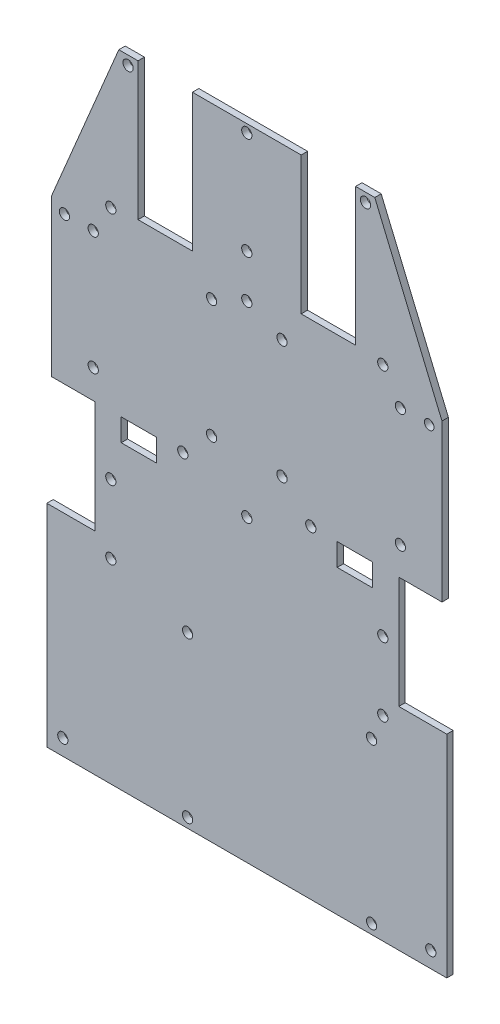
SolidWorks part; units mm, degrees
ref_plane "前基準面" through (0, 0, 0) normal (0, 0, 1) x (1, 0, 0)
ref_plane "上基準面" through (0, 0, 0) normal (0, 1, 0) x (1, 0, 0)
ref_plane "右基準面" through (0, 0, 0) normal (1, 0, 0) x (0, 0, -1)
sketch "草圖1" plane through (0, 0, 0) normal (0, 0, 1) x (1, 0, 0)
  line L0 (-42.5, 0) -> (42.5, 0)
  line L1 (-42.5, 0) -> (-42.5, 56)
  line L2 (-42.5, 56) -> (42.5, 56)
  line L3 (42.5, 56) -> (42.5, 0)
  line L4 (42.5, 0) -> (62.5, 0)
  line L5 (-42.5, 0) -> (-62.5, 0)
  line L6 (-62.5, 0) -> (-62.5, 66)
  line L7 (62.5, 0) -> (62.5, 66)
  line L8 (-62.5, 66) -> (-47.5, 66)
  line L9 (62.5, 66) -> (47.5, 66)
  line L10 (-47.5, 66) -> (-47.5, 101)
  line L12 (47.5, 101) -> (47.5, 66)
  line L16 (-62.5, 0) -> (-90.3643, 0)
  line L17 (-90.3643, 0) -> (-90.3643, 200)
  line L18 (-47.5, 101) -> (-61, 101)
  line L19 (47.5, 101) -> (61, 101)
  line L28 (-61, 101) -> (-61, 150)
  line L29 (-39.25, 101) -> (-28.25, 101)
  line L30 (39.25, 94) -> (28.25, 94)
  line L31 (-39.25, 101) -> (-39.25, 94)
  line L32 (-39.25, 94) -> (-28.25, 94)
  line L33 (-28.25, 101) -> (-28.25, 94)
  line L34 (28.25, 101) -> (28.25, 94)
  line L35 (39.25, 101) -> (28.25, 101)
  line L36 (39.25, 101) -> (39.25, 94)
  line L37 (61, 101) -> (61, 150)
  line L38 (62.5, 0) -> (90.3643, 0)
  line L39 (90.3643, 0) -> (90.3643, 200)
  line L40 (51, 107) -> (8, 107)
  line L41 (-51, 150) -> (-8, 150)
  line L42 (34, 200) -> (40, 200)
  line L43 (-51, 150) -> (-51, 107)
  line L44 (-51, 107) -> (-8, 107)
  line L45 (-8, 150) -> (-8, 107)
  line L46 (8, 150) -> (8, 107)
  line L47 (51, 150) -> (8, 150)
  line L48 (51, 150) -> (51, 107)
  line L49 (-17, 157) -> (-17, 200)
  line L50 (17, 157) -> (17, 200)
  line L52 (17, 157) -> (34, 157)
  line L53 (34, 157) -> (34, 200)
  line L54 (40, 200) -> (61, 150)
  line L55 (-90.3643, 200) -> (-40, 200)
  line L56 (-40, 200) -> (-61, 150)
  line L57 (-34, 200) -> (-40, 200)
  line L58 (-34, 157) -> (-34, 200)
  line L59 (-17, 157) -> (-34, 157)
  line L60 (-34, 200) -> (34, 200)
  line L62 (40, 200) -> (90.3643, 200)
  line L80 (62.5, 0) -> (62.5, -5)
  circle A0 centre (-48, 147) radius 1.6
  circle A1 centre (-48, 110) radius 1.6
  circle A2 centre (-11, 147) radius 1.6
  circle A3 centre (-11, 110) radius 1.6
  circle A4 centre (11, 147) radius 1.6
  circle A5 centre (47.9967, 147) radius 1.6
  circle A6 centre (47.9967, 110) radius 1.6
  circle A7 centre (11, 110) radius 1.6
  circle A10 centre (56.9967, 147.0085) radius 1.5
  circle A11 centre (37.0994, 197.2091) radius 1.6
  circle A12 centre (-56.9967, 147.0085) radius 1.6
  circle A13 centre (-37.0994, 197.2091) radius 1.6
  circle A16 centre (-18.5, 53) radius 1.6
  circle A17 centre (-18.5, 3) radius 1.6
  circle A18 centre (39, 53) radius 1.6
  circle A19 centre (39, 3) radius 1.6
  circle A22 centre (42.5, 61) radius 1.6
  circle A23 centre (-42.5, 61) radius 1.6
  circle A24 centre (0, 197.5) radius 1.6
  circle A25 centre (0, 165.5) radius 1.6
  circle A31 centre (42.5, 156) radius 1.6
  circle A32 centre (-42.5, 156) radius 1.6
  circle A33 centre (0, 93.5) radius 1.6
  circle A34 centre (57.5, 5) radius 1.6
  circle A35 centre (-57.5, 5) radius 1.6
  circle A36 centre (42.5, 82.5) radius 1.6
  circle A37 centre (-42.5, 82.5) radius 1.6
  circle A39 centre (-20, 101) radius 1.6
  circle A40 centre (20, 101) radius 1.6
  circle A45 centre (0, 152) radius 1.6
  point P4 (0, 0)
  dimension "D1" = 43
  dimension "D8" = 15
  dimension "D23" = 3.2
  dimension "D20" = 10
  dimension "D34" = 3.2
  dimension "D35" = 3.2
  dimension "D36" = 3.2
  dimension "D37" = 3.2
  dimension "D38" = 4.0033
  dimension "D39" = 3
  dimension "D40" = 37
  dimension "D41" = 3.2
  dimension "D42" = 3
  dimension "D43" = 37
  dimension "D44" = 3.2
  dimension "D45" = 3.2
  dimension "D46" = 3.2
  dimension "D47" = 3.2
  dimension "D48" = 3.2
  dimension "D49" = 3.2
  dimension "D54" = 3
  dimension "D56" = 3.2
  dimension "D59" = 3.2
  dimension "D61" = 3.2
  dimension "D62" = 3.2
  dimension "D64" = 3.2
  dimension "D67" = 85
  dimension "D73" = 3.2
  dimension "D74" = 3.2
  dimension "D72" = 3.2
  dimension "D78" = 61
  dimension "D82" = 3.2
  dimension "D83" = 3.2
  dimension "D87" = 3.2
  dimension "D88" = 3.2
  dimension "D92" = 3.2
  dimension "D93" = 3.2
  dimension "D96" = 5
  dimension "D2" = 43
  dimension "D3" = 85
  dimension "D4" = 56
  dimension "D5" = 66
  dimension "D6" = 20
  dimension "D7" = 20
  dimension "D9" = 35
  dimension "D10" = 8.25
  dimension "D11" = 8.25
  dimension "D12" = 13.5
  dimension "D13" = 49
  dimension "D14" = 54.231
  dimension "D15" = 50
  dimension "D16" = 50
  dimension "D17" = 6
  dimension "D18" = 43
  dimension "D19" = 17
  dimension "D21" = 3
  dimension "D22" = 24
  dimension "D24" = 57.5
  dimension "D25" = 50
  dimension "D26" = 10
  dimension "D27" = 7
  dimension "D28" = 11
  dimension "D29" = 6
  dimension "D30" = 38
  dimension "D31" = 11
  dimension "D32" = 38
  dimension "D33" = 7
  dimension "D50" = 3.0994
  dimension "D51" = 2.7909
  dimension "D52" = 3.0994
  dimension "D53" = 4.0033
  dimension "D55" = 46.0085
  dimension "D57" = 3
  dimension "D58" = 3
  dimension "D60" = 3
  dimension "D63" = 36.9967
  dimension "D65" = 47.5
  dimension "D66" = 6
  dimension "D68" = 8.5
  dimension "D69" = 37.5
  dimension "D70" = 34.5
  dimension "D71" = 2.5
  dimension "D75" = 20
  dimension "D76" = 20
  dimension "D77" = 5
  dimension "D79" = 5
  dimension "D84" = 41
  dimension "D85" = 41
  dimension "D86" = 6
  dimension "D89" = 20
  dimension "D90" = 20
  dimension "D91" = 26.5
  dimension "D94" = 5
  dimension "D95" = 5
extrude "填料-伸長1" add sketch "草圖1" along normal blind 2 contours L60 L49 L59 L58 L57 L56 L28 L18 L10 L8 L6 L5 L1 L2 L3 L4 L7 L9 L12 L19 L37 L54 L42 L53 L52 L50 A39 A35 A34 A33 A32 A31 A25 A24 A23 A22 A12 A11 | L45 L41 L43 L44 A3 A2 A1 A0 | L48 L47 L46 L40 A6 A4 A5 A7 | L3 L2 L1 L0 A17 A16 A18 A19
